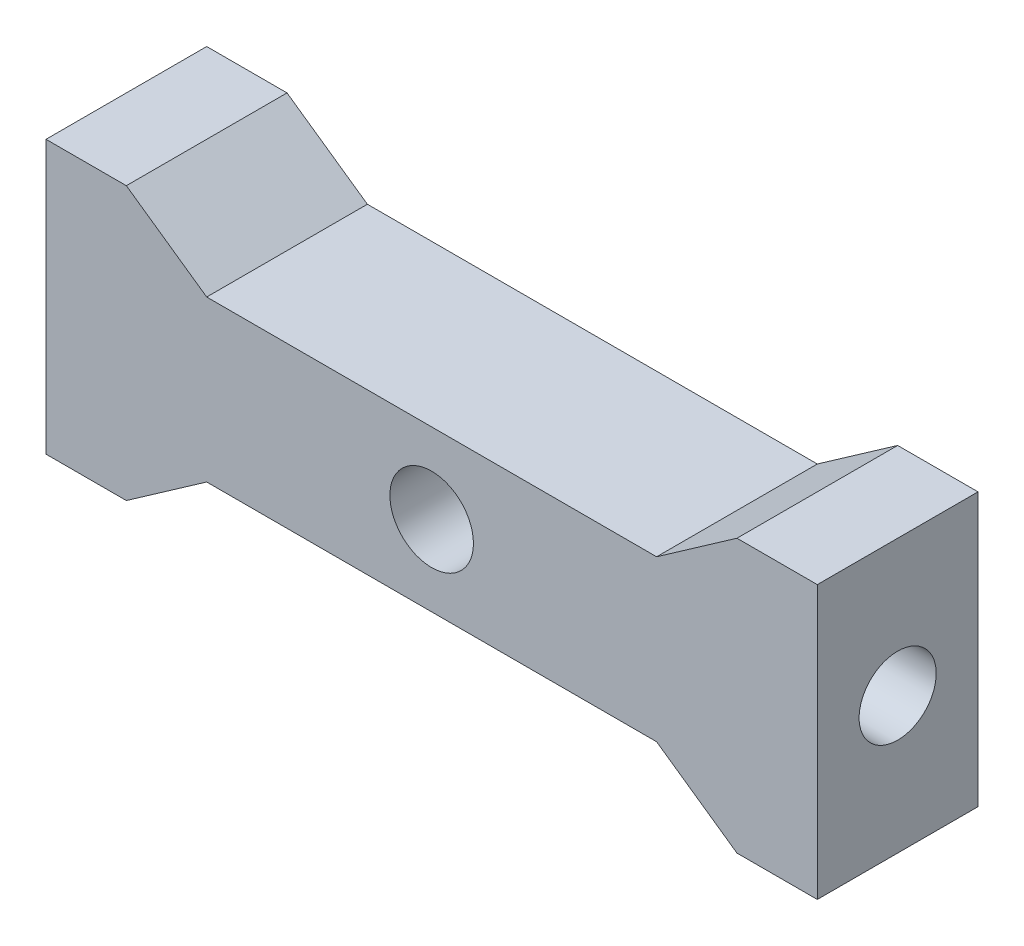
SolidWorks part; units mm, degrees
ref_plane "正面" through (0, 0, 0) normal (0, 0, 1) x (1, 0, 0)
ref_plane "平面" through (0, 0, 0) normal (0, 1, 0) x (1, 0, 0)
ref_plane "右側面" through (0, 0, 0) normal (1, 0, 0) x (0, 0, -1)
sketch "ｽｹｯﾁ1" plane through (0, 0, 0) normal (0, 0, 1) x (1, 0, 0)
  line L1 (-24, 8.485) -> (24, 8.485)
  line L2 (-24, 8.485) -> (-24, -8.485)
  line L3 (-24, -8.485) -> (24, -8.485)
  line L4 (24, 8.485) -> (24, -8.485)
  line L5 (-24, 8.485) -> (24, -8.485) construction
  line L6 (-24, -8.485) -> (24, 8.485) construction
  circle A0 centre (0, 0) radius 2.6
  dimension "D1" = 5.2
  dimension "D2" = 16.97
  dimension "D3" = 48
extrude "ﾎﾞｽ - 押し出し1" add sketch "ｽｹｯﾁ1" along normal blind 10
sketch "ｽｹｯﾁ3" plane through (24, 0, 0) normal (1, 0, 0) x (0, 0, -1)
  circle A0 centre (-5, 0) radius 2.4
  dimension "D1" = 4.8
extrude "ｶｯﾄ - 押し出し1" cut sketch "ｽｹｯﾁ3" against normal blind 6
sketch "ｽｹｯﾁ4" plane through (-24, 0, 0) normal (-1, 0, 0) x (0, 0, 1)
  circle A0 centre (5, 0) radius 2.4
  dimension "D1" = 4.8
extrude "ｶｯﾄ - 押し出し2" cut sketch "ｽｹｯﾁ4" against normal blind 6
sketch "ｽｹｯﾁ5" plane through (0, 0, 10) normal (0, 0, 1) x (1, 0, 0)
  line L0 (-14, 4.985) -> (14, 4.985)
  line L1 (14, 4.985) -> (19, 8.485)
  line L2 (24, 8.485) -> (-24, 8.485) construction
  line L3 (-14, 4.985) -> (-19, 8.485)
  line L4 (-19, 8.485) -> (19, 8.485)
  line L5 (-14, -4.985) -> (14, -4.985)
  line L6 (14, -4.985) -> (19, -8.485)
  line L7 (-24, -8.485) -> (24, -8.485) construction
  line L8 (19, -8.485) -> (-19, -8.485)
  line L9 (-19, -8.485) -> (-14, -4.985)
  line L10 (24, -8.485) -> (24, 8.485) construction
  line L11 (-24, 8.485) -> (-24, -8.485) construction
  dimension "D1" = 3.5
  dimension "D2" = 3.5
  dimension "D3" = 5
  dimension "D4" = 5
  dimension "D5" = 5
  dimension "D6" = 5
extrude "ｶｯﾄ - 押し出し3" cut sketch "ｽｹｯﾁ5" against normal through all
